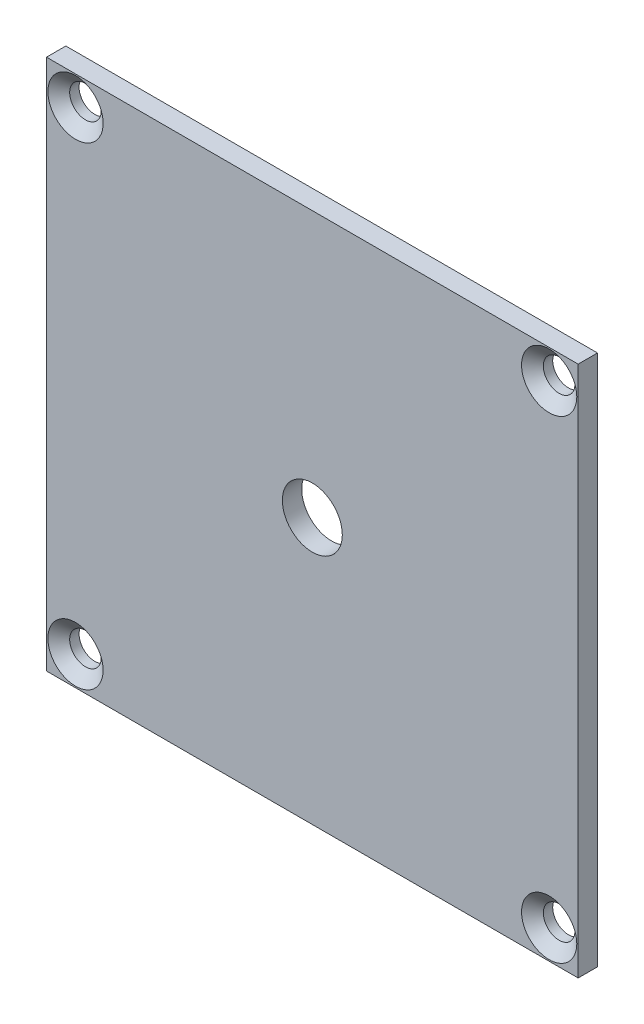
SolidWorks part; units mm, degrees
ref_plane "Front Plane" through (0, 0, 0) normal (0, 0, 1) x (1, 0, 0)
ref_plane "Top Plane" through (0, 0, 0) normal (0, 1, 0) x (1, 0, 0)
ref_plane "Right Plane" through (0, 0, 0) normal (1, 0, 0) x (0, 0, -1)
sketch "Sketch1" plane through (0, 0, 0) normal (0, 0, 1) x (1, 0, 0)
  line L1 (0, 0) -> (55, 0)
  line L2 (0, 0) -> (0, 55)
  line L3 (0, 55) -> (55, 55)
  line L4 (55, 0) -> (55, 55)
  dimension "D1" = 55
  dimension "D2" = 55
extrude "Boss-Extrude1" add sketch "Sketch1" along normal blind 2
sketch "Sketch2" plane through (0, 0, 2) normal (0, 0, 1) x (1, 0, 0)
  line L0 (0, 27.5) -> (55, 27.5) construction
  line L1 (0, 55) -> (0, 0) construction
  line L2 (55, 0) -> (55, 55) construction
  line L3 (3, 52) -> (52, 52) construction
  line L4 (52, 52) -> (52, 3) construction
  line L5 (52, 3) -> (3, 3) construction
  line L6 (3, 3) -> (3, 52) construction
  line L7 (27.5, 0) -> (27.5, 55) construction
  line L8 (0, 0) -> (55, 0) construction
  line L9 (55, 55) -> (0, 55) construction
  point P8 (27.5, 52)
  point P11 (3, 27.5)
  dimension "D1" = 49
  dimension "D2" = 49
sketch "Sketch3" plane through (0, 0, 2) normal (0, 0, 1) x (1, 0, 0)
  line L0 (0, 27.5) -> (55, 27.5) construction
  circle A0 centre (27.5, 27.5) radius 3.1
  dimension "D1" = 6.2
extrude "Cut-Extrude1" cut sketch "Sketch3" against normal through all
hole_wizard "CSK for #4 Flat Head Machine Screw (100)1" positions "Sketch4" profile "Sketch5" countersink size "#4" standard "Superior" end condition through all
sketch "Sketch4" plane through (0, 0, 2) normal (0, 0, 1) x (1, 0, 0)
  point P0 (3, 52)
  point P3 (52, 52)
  point P6 (52, 3)
  point P9 (3, 3)
sketch "Sketch5" plane through (3, 52, 2) normal (1, 0, 0) x (0, -1, 0)
  line L0 (0, 0) -> (0, 2)
  line L1 (0, 2) -> (1.632, 2)
  line L2 (1.632, 2) -> (1.6319, 1.0284)
  line L3 (1.6319, 1.0284) -> (2.8575, 0)
  line L5 (2.8575, 0) -> (0, 0)
  line L6 (-1.6319, 1.0284) -> (-2.8575, 0) construction
  line L11 (0, -6.35) -> (0, 107.95) construction
  dimension "Thru Hole Dia." = 3.2639
  dimension "Thru Hole Depth" = 2
  dimension "Near C'Sink Dia." = 5.715
  dimension "Near C'Sink Angle" = 100
